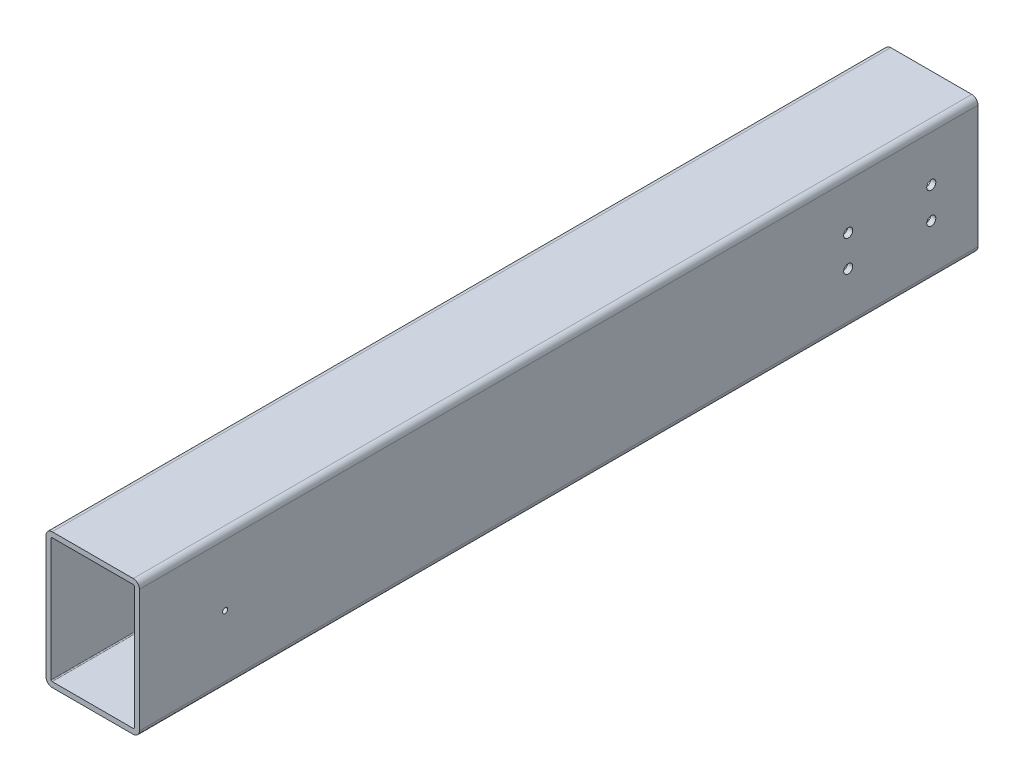
SolidWorks part; units mm, degrees
ref_plane "Front Plane" through (0, 0, 0) normal (0, 0, 1) x (1, 0, 0)
ref_plane "Top Plane" through (0, 0, 0) normal (0, 1, 0) x (1, 0, 0)
ref_plane "Right Plane" through (0, 0, 0) normal (1, 0, 0) x (0, 0, -1)
sketch "Sketch2" plane through (0, 0, 0) normal (1, 0, 0) x (0, 0, -1)
  line L0 (807.5, 0) -> (-807.5, 0)
  point P4 (0, 0)
  dimension "D1" = 1615
other "Tube square TS3X3X0.3125(1)"
ref_plane "Plane1" through (0, 0, -807.5) normal (0, 0, 1) x (0, -1, 0)
sketch "Sketch14" plane through (0, 0, -807.5) normal (0, 0, 1) x (0, -1, 0)
  line L0 (-118, -80) -> (118, -80)
  line L1 (-120, -78) -> (-120, 78)
  line L2 (118, 80) -> (-118, 80)
  line L3 (120, 78) -> (120, -78)
  line L4 (-118, -90) -> (118, -90)
  line L5 (-130, -78) -> (-130, 78)
  line L6 (118, 90) -> (-118, 90)
  line L7 (130, 78) -> (130, -78)
  line L8 (-130, 0) -> (-120, 0) construction
  line L9 (-120, 0) -> (120, 0) construction
  line L10 (120, 0) -> (130, 0) construction
  line L11 (0, 90) -> (0, 80) construction
  line L12 (0, 80) -> (0, -80) construction
  line L13 (0, -80) -> (0, -90) construction
  arc A0 (130, 78) -> (118, 90) centre (118, 78) ccw
  arc A1 (118, -90) -> (130, -78) centre (118, -78) ccw
  arc A2 (-130, -78) -> (-118, -90) centre (-118, -78) ccw
  arc A3 (-118, 90) -> (-130, 78) centre (-118, 78) ccw
  arc A4 (-118, 80) -> (-120, 78) centre (-118, 78) ccw
  arc A5 (120, 78) -> (118, 80) centre (118, 78) ccw
  arc A6 (118, -80) -> (120, -78) centre (118, -78) ccw
  arc A7 (-120, -78) -> (-118, -80) centre (-118, -78) ccw
  point P6 (-130, -90)
  point P33 (-130, 90)
  point P35 (130, 90)
  point P36 (130, -90)
  point P37 (0, 0)
  point P38 (0, 0)
  dimension "D1" = 12
  dimension "Thickness" = 10
  dimension "V_leg" = 180
  dimension "H_leg" = 260
sketch "Sketch15" plane through (0, -130, 0) normal (0, -1, 0) x (1, 0, 0)
  line L0 (0, -807.5) -> (0, 807.5) construction
  line L1 (4, -807.5) -> (-4, -807.5)
  line L2 (4, -807.5) -> (4, 592.5)
  line L3 (4, 592.5) -> (-4, 592.5)
  line L4 (-4, -807.5) -> (-4, 592.5)
  line L6 (-78, -807.5) -> (78, -807.5) construction
  point P4 (0, 592.5)
  dimension "D1" = 8
  dimension "D2" = 1400
sketch "Sketch16" plane through (90, 0, 0) normal (1, 0, 0) x (0, 0, -1)
  line L0 (807.5, -118) -> (807.5, 118) construction
  line L1 (557.5, 30) -> (717.5, 30)
  line L2 (557.5, 30) -> (557.5, -30)
  line L3 (557.5, -30) -> (717.5, -30)
  line L4 (717.5, 30) -> (717.5, -30)
  point P6 (807.5, 0)
  point P7 (717.5, 0)
  dimension "D1" = 250
  dimension "D2" = 160
  dimension "D3" = 60
hole_wizard "M20x2.5 Tapped Hole1" positions "Sketch17" profile "Sketch18" tap size "M20x2.5" standard "ANSI Metric" end condition through all
sketch "Sketch17" plane through (90, 0, 0) normal (1, 0, 0) x (0, 0, -1)
  point P0 (717.5, 30)
  point P3 (557.5, 30)
  point P6 (557.5, -30)
  point P9 (717.5, -30)
sketch "Sketch18" plane through (90, 30, -717.5) normal (0, 1, 0) x (0, 0, -1)
  line L0 (0, 0) -> (0, 180)
  line L1 (0, 180) -> (8.75, 180)
  line L2 (8.75, 180) -> (8.75, 0)
  line L5 (8.75, 0) -> (0, 0)
  line L11 (0, -6.35) -> (0, 107.95) construction
  dimension "Thru Tap Drill Dia." = 17.5
  dimension "Thru Tap Drill Depth" = 180
sketch "Sketch19" plane through (90, 0, 0) normal (1, 0, 0) x (0, 0, -1)
  line L0 (-807.5, -118) -> (-807.5, 118) construction
  line L1 (-642.5, 0) -> (-807.5, 0) construction
  circle A0 centre (-642.5, 0) radius 5
  dimension "D1" = 10
  dimension "D2" = 165
extrude "Cut-Extrude1" cut sketch "Sketch19" against normal through all
